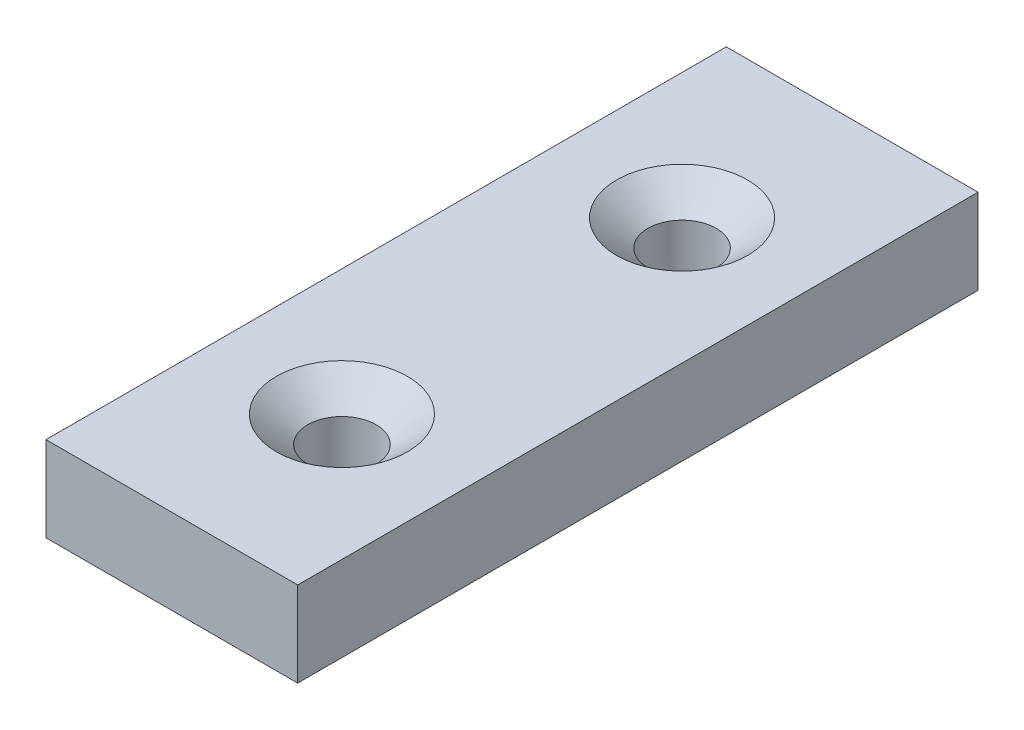
SolidWorks part; units mm, degrees
material "ABS"
ref_plane "Front Plane" through (0, 0, 0) normal (0, 0, 1) x (1, 0, 0)
ref_plane "Top Plane" through (0, 0, 0) normal (0, 1, 0) x (1, 0, 0)
ref_plane "Right Plane" through (0, 0, 0) normal (1, 0, 0) x (0, 0, -1)
sketch "Sketch1" plane through (0, 0, 0) normal (0, 1, 0) x (1, 0, 0)
  line L1 (0, 0) -> (18.796, 0)
  line L2 (0, 0) -> (0, 50.8)
  line L3 (0, 50.8) -> (18.796, 50.8)
  line L4 (18.796, 0) -> (18.796, 50.8)
  dimension "D1" = 50.8
  dimension "D2" = 18.796
extrude "Boss-Extrude1" add sketch "Sketch1" along normal blind 6.35
sketch "Sketch2" plane through (0, 6.35, 0) normal (0, 1, 0) x (1, 0, 0)
  line L0 (9.398, 0) -> (9.398, 50.8) construction
  line L1 (0, 0) -> (18.796, 0) construction
  line L2 (18.796, 50.8) -> (0, 50.8) construction
  line L3 (9.398, 25.4) -> (12.7712, 25.4) construction
  circle A0 centre (9.398, 38.1) radius 2.2471
  circle A1 centre (9.398, 12.7) radius 2.2471
  dimension "D1" = 12.7
hole_wizard "CSK for #10 Flat Head Machine Screw (100)1" positions "Sketch3" profile "Sketch4" countersink size "#10" standard "ANSI Inch"
sketch "Sketch3" plane through (0, 6.35, 0) normal (0, 1, 0) x (1, 0, 0)
  point P0 (9.398, 38.1)
  point P3 (9.398, 12.7)
sketch "Sketch4" plane through (9.398, 6.35, -38.1) normal (1, 0, 0) x (0, 0, 1)
  line L0 (0, 0) -> (0, 26.9338)
  line L1 (0, 26.9338) -> (2.5527, 25.4)
  line L2 (2.5527, 25.4) -> (2.5527, 1.9608)
  line L3 (2.5527, 1.9608) -> (4.8895, 0)
  line L5 (4.8895, 0) -> (0, 0)
  line L6 (-2.5527, 1.9608) -> (-4.8895, 0) construction
  line L10 (0, 26.9338) -> (-2.5527, 25.4) construction
  line L11 (0, -6.35) -> (0, 107.95) construction
  dimension "Hole Dia." = 5.1054
  dimension "Hole Depth" = 25.4
  dimension "Near C'Sink Dia." = 9.779
  dimension "Near C'Sink Angle" = 100
  dimension "Drill Angle" = 118
